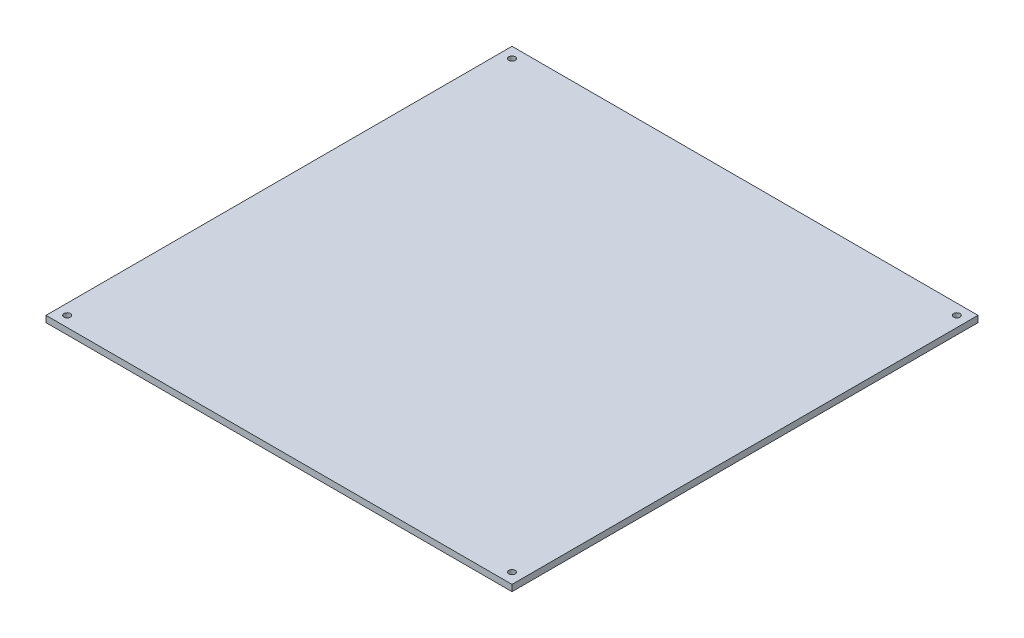
SolidWorks part; units mm, degrees
ref_plane "前视基准面" through (0, 0, 0) normal (0, 0, 1) x (1, 0, 0)
ref_plane "上视基准面" through (0, 0, 0) normal (0, 1, 0) x (1, 0, 0)
ref_plane "右视基准面" through (0, 0, 0) normal (1, 0, 0) x (0, 0, -1)
sketch "草图1" plane through (0, 0, 0) normal (0, 1, 0) x (1, 0, 0)
  line L1 (0, 0) -> (-220, 0)
  line L2 (0, 0) -> (0, -220)
  line L3 (0, -220) -> (-220, -220)
  line L4 (-220, 0) -> (-220, -220)
  line L5 (0, 0) -> (-220, -220) construction
  line L6 (0, -220) -> (-220, 0) construction
  line L7 (-5, -215) -> (-215, -215) construction
  line L8 (-5, -215) -> (-5, -5) construction
  line L9 (-5, -5) -> (-215, -5) construction
  line L10 (-215, -215) -> (-215, -5) construction
  line L11 (-110, -5) -> (-110, -215) construction
  line L12 (-5, -110) -> (-215, -110) construction
  circle A0 centre (-215, -5) radius 1.5
  circle A1 centre (-5, -5) radius 1.5
  circle A2 centre (-5, -215) radius 1.5
  circle A3 centre (-215, -215) radius 1.5
  point P4 (-110, -110)
  point P6 (-110, -110)
  dimension "D4" = 3
  dimension "D1" = 220
  dimension "D2" = 220
  dimension "D3" = 210
extrude "凸台-拉伸1" add sketch "草图1" along normal blind 3
